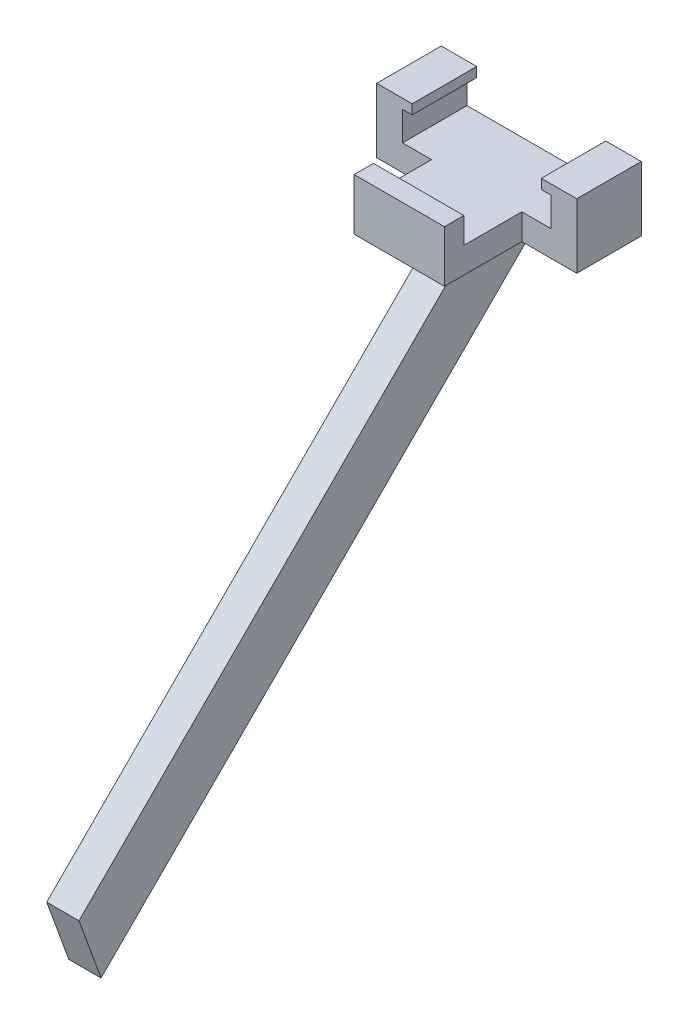
SolidWorks part; units mm, degrees
ref_plane "Front Plane" through (0, 0, 0) normal (0, 0, 1) x (1, 0, 0)
ref_plane "Top Plane" through (0, 0, 0) normal (0, 1, 0) x (1, 0, 0)
ref_plane "Right Plane" through (0, 0, 0) normal (1, 0, 0) x (0, 0, -1)
sketch "Sketch1" plane through (0, 0, 0) normal (0, 0, 1) x (1, 0, 0)
  line L0 (0, 0) -> (0, -9)
  line L1 (0, -9) -> (31, -9)
  line L2 (31, -9) -> (31, 0)
  line L4 (27, -0.5) -> (27, -5)
  line L5 (27, -5) -> (4, -5)
  line L6 (4, -5) -> (4, -0.5)
  line L8 (0, 0) -> (0, 1)
  line L9 (0, 1) -> (5.5, 1)
  line L10 (5.5, 1) -> (5.5, -0.5)
  line L11 (5.5, -0.5) -> (4, -0.5)
  line L12 (15.5, -9) -> (15.5, 2.6509) construction
  line L13 (0, 0) -> (0, 1)
  line L14 (31, 0) -> (31, 1)
  line L15 (25.5, -0.5) -> (27, -0.5)
  line L16 (25.5, 1) -> (25.5, -0.5)
  line L17 (31, 1) -> (25.5, 1)
  dimension "D1" = 23
  dimension "D3" = 4
  dimension "D5" = 1.5
  dimension "D7" = 5.5
extrude "Boss-Extrude1" add sketch "Sketch1" along normal blind 10 contours L1 L12 L5 L6 L11 L10 L9 L8 L0 | L12 L1 L2 L14 L17 L16 L15 L4 L5
ref_plane "Plane1" through (15.5, 0, 0) normal (-1, 0, 0) x (0, 0, 1)
sketch "Sketch2" plane through (15.5, 0, 0) normal (-1, 0, 0) x (0, 0, 1)
  line L0 (0, -9) -> (70.7107, -79.7107)
  line L1 (70.7107, -79.7107) -> (74.1309, -70.3138)
  line L2 (74.1309, -70.3138) -> (12.8171, -9)
  line L3 (10, -9) -> (0, -9) construction
  line L4 (74.1309, -70.3138) -> (74.1309, -99.7264) construction
  line L5 (74.1309, -70.3138) -> (74.1309, -44.9818) construction
  line L6 (70.7107, -79.7107) -> (70.7107, -67.2547) construction
  line L11 (0, 1) -> (0, -9)
  line L12 (0, -9) -> (10, -9)
  line L13 (10, -9) -> (10, 1)
  line L14 (10, 1) -> (0, 1)
  line L16 (0, -9) -> (12.8171, -9)
  dimension "D1" = 20
  dimension "D2" = 45
  dimension "D3" = 45
  dimension "D5" = 100
  dimension "D6" = 10
  dimension "D4" = 0
extrude "Boss-Extrude2" add sketch "Sketch2" along normal mid plane 5
sketch "Sketch9" plane through (0, -9, 0) normal (0, 1, 0) x (1, 0, 0)
  line L0 (8.5, -10) -> (8.5, -19)
  line L1 (27, -10) -> (4, -10) construction
  line L2 (8.5, -19) -> (22.5, -19)
  line L3 (22.5, -19) -> (22.5, -10)
  line L4 (22.5, -10) -> (8.5, -10)
  line L5 (15.5, -10) -> (15.5, -19) construction
  line L6 (27, 0) -> (4, 0) construction
  point P10 (15.5, 0)
  dimension "D1" = 9
  dimension "D2" = 7
  dimension "D3" = 7
extrude "Boss-Extrude11" add sketch "Sketch9" along normal blind 4
sketch "Sketch10" plane through (0, 0, 19) normal (0, 0, 1) x (1, 0, 0)
  line L1 (8.5, -9) -> (22.5, -9)
  line L2 (8.5, -9) -> (8.5, -1)
  line L3 (8.5, -1) -> (22.5, -1)
  line L4 (22.5, -9) -> (22.5, -1)
  dimension "D1" = 8
extrude "Boss-Extrude12" add sketch "Sketch10" along normal blind 3
sketch "Sketch11" plane through (0, -32.0504, 88.0576) normal (0, -0.342, 0.9397) x (1, 0, 0)
  line L0 (41.3296, -45.7191) -> (-10.1927, -45.7191) construction
  line L1 (41.3296, -50.7138) -> (-10.1927, -50.7138)
  line L2 (41.3296, -40.7243) -> (-10.1927, -40.7243)
  line L3 (15.5685, -60.9797) -> (15.5685, -30.4584) construction
  line L4 (12.9738, -60.9797) -> (12.9738, -30.4584)
  line L5 (18.1632, -60.9797) -> (18.1632, -30.4584)
  arc A0 (41.3296, -50.7138) -> (41.3296, -40.7243) centre (41.3296, -45.7191) ccw
  arc A1 (-10.1927, -40.7243) -> (-10.1927, -50.7138) centre (-10.1927, -45.7191) ccw
  arc A2 (12.9738, -60.9797) -> (18.1632, -60.9797) centre (15.5685, -60.9797) ccw
  arc A3 (18.1632, -30.4584) -> (12.9738, -30.4584) centre (15.5685, -30.4584) ccw
  point P2 (15.5685, -45.7191)
  point P9 (15.5685, -45.7191)
sketch "Sketch14" plane through (31, 0, 0) normal (1, 0, 0) x (0, 0, -1)
  line L1 (-24.7599, -9) -> (9.7094, -9)
  line L2 (-24.7599, -9) -> (-24.7599, 4.4744)
  line L3 (-24.7599, 4.4744) -> (9.7094, 4.4744)
  line L4 (9.7094, -9) -> (9.7094, 4.4744)
